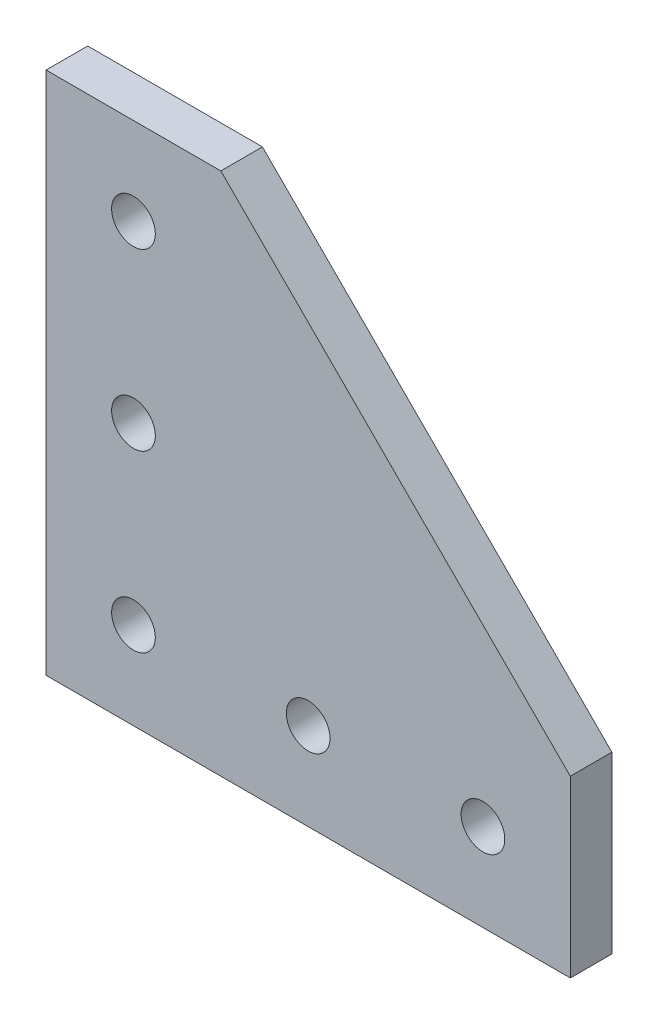
SolidWorks part; units mm, degrees
material "6063-T5"
ref_plane "Front Plane" through (0, 0, 0) normal (0, 0, 1) x (1, 0, 0)
ref_plane "Top Plane" through (0, 0, 0) normal (0, 1, 0) x (1, 0, 0)
ref_plane "Right Plane" through (0, 0, 0) normal (1, 0, 0) x (0, 0, -1)
sketch "Sketch1" plane through (0, 0, 0) normal (0, 0, 1) x (1, 0, 0)
  line L0 (0, 0) -> (0, 60)
  line L1 (0, 60) -> (20, 60)
  line L2 (0, 0) -> (60, 0)
  line L3 (60, 0) -> (60, 20)
  line L4 (20, 60) -> (60, 20)
  line L5 (20, 60) -> (20, 20) construction
  line L6 (60, 20) -> (20, 20) construction
  line L7 (10, 10) -> (0, 10) construction
  line L8 (10, 10) -> (10, 0) construction
  circle A0 centre (10, 10) radius 2.5
  circle A1 centre (30, 10) radius 2.5
  circle A2 centre (50, 10) radius 2.5
  circle A3 centre (10, 30) radius 2.5
  circle A4 centre (10, 50) radius 2.5
  dimension "D3" = 5
  dimension "D4" = 10
  dimension "D1" = 20
  dimension "D2" = 60
  dimension "D5" = 3
  dimension "D6" = 3
extrude "Boss-Extrude1" add sketch "Sketch1" along normal blind 4.7625
